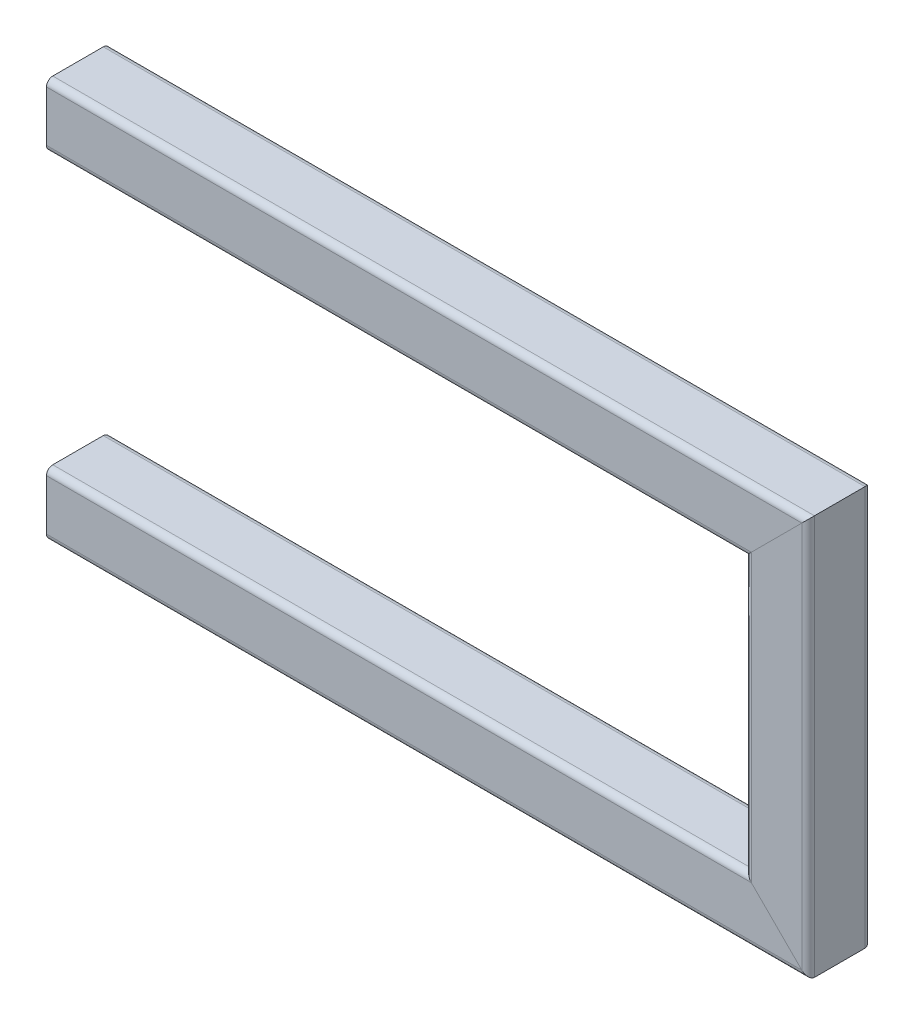
SolidWorks part; units mm, degrees
ref_plane "Plan de face" through (0, 0, 0) normal (0, 0, 1) x (1, 0, 0)
ref_plane "Plan de dessus" through (0, 0, 0) normal (0, 1, 0) x (1, 0, 0)
ref_plane "Plan de droite" through (0, 0, 0) normal (1, 0, 0) x (0, 0, -1)
sketch "Esquisse1" plane through (0, 0, 0) normal (0, 0, 1) x (1, 0, 0)
  line L0 (0, 0) -> (347, 0)
  line L1 (347, 0) -> (347, 160)
  line L2 (347, 160) -> (0, 160)
  point P3 (0, 0)
  point P6 (0, 0)
  dimension "D1" = 347
  dimension "D2" = 160
sketch "Esquisse2" plane through (0, 0, 0) normal (1, 0, 0) x (0, 0, -1)
  line L1 (-12, -15) -> (12, -15)
  line L2 (-15, -12) -> (-15, 12)
  line L3 (-12, 15) -> (12, 15)
  line L4 (15, -12) -> (15, 12)
  line L5 (0, 15) -> (0, -15) construction
  line L6 (-15, 0) -> (15, 0) construction
  line L7 (-10, -13) -> (10, -13)
  line L8 (-13, -10) -> (-13, 10)
  line L9 (-10, 13) -> (10, 13)
  line L10 (13, -10) -> (13, 10)
  line L11 (0, 13) -> (0, -13) construction
  line L12 (-13, 0) -> (13, 0) construction
  arc A0 (10, -13) -> (13, -10) centre (10, -10) ccw
  arc A1 (12, -15) -> (15, -12) centre (12, -12) ccw
  arc A2 (-13, 10) -> (-10, 13) centre (-10, 10) cw
  arc A3 (-10, -13) -> (-13, -10) centre (-10, -10) cw
  arc A4 (10, 13) -> (13, 10) centre (10, 10) cw
  arc A5 (-12, -15) -> (-15, -12) centre (-12, -12) cw
  arc A6 (12, 15) -> (15, 12) centre (12, 12) cw
  arc A7 (-15, 12) -> (-12, 15) centre (-12, 12) cw
  point P0 (0, 0)
  point P4 (0, 0)
  point P13 (13, -13)
  point P19 (15, -15)
  point P22 (-13, 13)
  point P27 (13, 13)
  point P32 (15, 15)
  point P35 (-15, 15)
  dimension "D5" = 3
  dimension "D1" = 30
  dimension "D2" = 30
  dimension "D3" = 26
  dimension "D4" = 26
sweep "Balayage1" add profiles "Esquisse2" path "Esquisse1"
